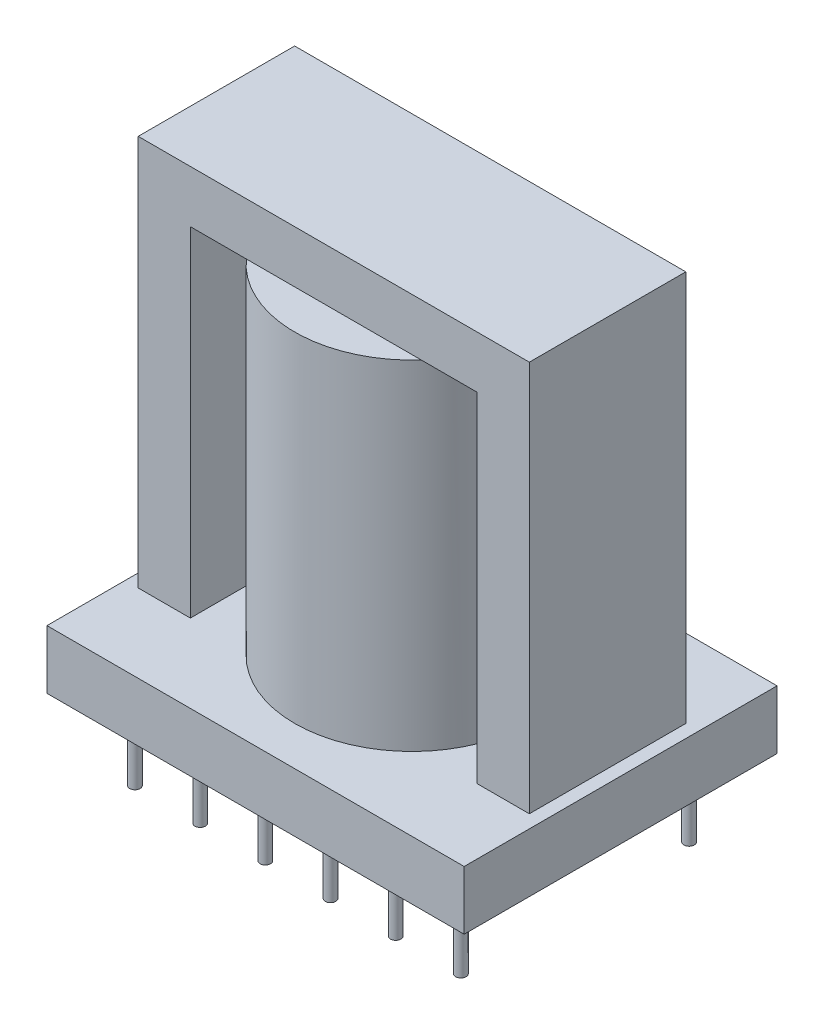
SolidWorks part; units mm, degrees
ref_plane "정면" through (0, 0, 0) normal (0, 0, 1) x (1, 0, 0)
ref_plane "윗면" through (0, 0, 0) normal (0, 1, 0) x (1, 0, 0)
ref_plane "우측면" through (0, 0, 0) normal (1, 0, 0) x (0, 0, -1)
sketch "스케치1" plane through (0, 0, 0) normal (0, 1, 0) x (1, 0, 0)
  line L0 (0, -50.1176) -> (0, 57.1765) construction
  line L1 (-66.1765, 0) -> (66.8824, 0) construction
  line L3 (-16, 12) -> (16, 12)
  line L4 (-16, 12) -> (-16, -12)
  line L5 (-16, -12) -> (16, -12)
  line L6 (16, 12) -> (16, -12)
  dimension "D1" = 12
  dimension "D2" = 12
  dimension "D3" = 16
  dimension "D4" = 16
extrude "보스-돌출1" add sketch "스케치1" along normal blind 4.5
sketch "스케치2" plane through (0, 4.5, 0) normal (0, 1, 0) x (1, 0, 0)
  line L0 (-13.0546, 0) -> (14.0487, 0) construction
  line L1 (0, 6.196) -> (0, -5.5996) construction
  line L2 (-15, 6) -> (-15, -6)
  line L3 (11, 6) -> (15, 6)
  line L4 (11, 6) -> (11, -6)
  line L5 (11, -6) -> (15, -6)
  line L6 (15, 6) -> (15, -6)
  line L7 (-11, -6) -> (-15, -6)
  line L8 (-11, 6) -> (-11, -6)
  line L9 (-11, 6) -> (-15, 6)
  circle A0 centre (0, 0) radius 9
  dimension "D5" = 18
  dimension "D1" = 15
  dimension "D2" = 6
  dimension "D3" = 6
  dimension "D4" = 11
extrude "보스-돌출2" add sketch "스케치2" along normal blind 26
sketch "스케치3" plane through (0, 30.5, 0) normal (0, 1, 0) x (1, 0, 0)
  line L1 (-15, 6) -> (15, 6)
  line L2 (-15, 6) -> (-15, -6)
  line L3 (-15, -6) -> (15, -6)
  line L4 (15, 6) -> (15, -6)
extrude "보스-돌출3" add sketch "스케치3" along normal blind 4
sketch "스케치4" plane through (0, 0, 0) normal (0, -1, 0) x (1, 0, 0)
  line L0 (-15.6722, 0) -> (15.2083, 0) construction
  line L1 (0, 11.7624) -> (0, -11.1329) construction
  circle A0 centre (2.5, -8.75) radius 0.4
  circle A1 centre (7.5, -8.75) radius 0.4
  circle A2 centre (12.5, -8.75) radius 0.4
  circle A3 centre (-12.5, -8.75) radius 0.4
  circle A4 centre (-7.5, -8.75) radius 0.4
  circle A5 centre (-2.5, -8.75) radius 0.4
  circle A6 centre (-2.5, 8.75) radius 0.4
  circle A7 centre (-7.5, 8.75) radius 0.4
  circle A8 centre (-12.5, 8.75) radius 0.4
  circle A9 centre (12.5, 8.75) radius 0.4
  circle A10 centre (7.5, 8.75) radius 0.4
  circle A11 centre (2.5, 8.75) radius 0.4
  dimension "D7" = 0.8
  dimension "D8" = 0.8
  dimension "D9" = 0.8
  dimension "D1" = 8.75
  dimension "D2" = 8.75
  dimension "D3" = 8.75
  dimension "D4" = 2.5
  dimension "D5" = 7.5
  dimension "D6" = 12.5
extrude "보스-돌출4" add sketch "스케치4" along normal blind 6
